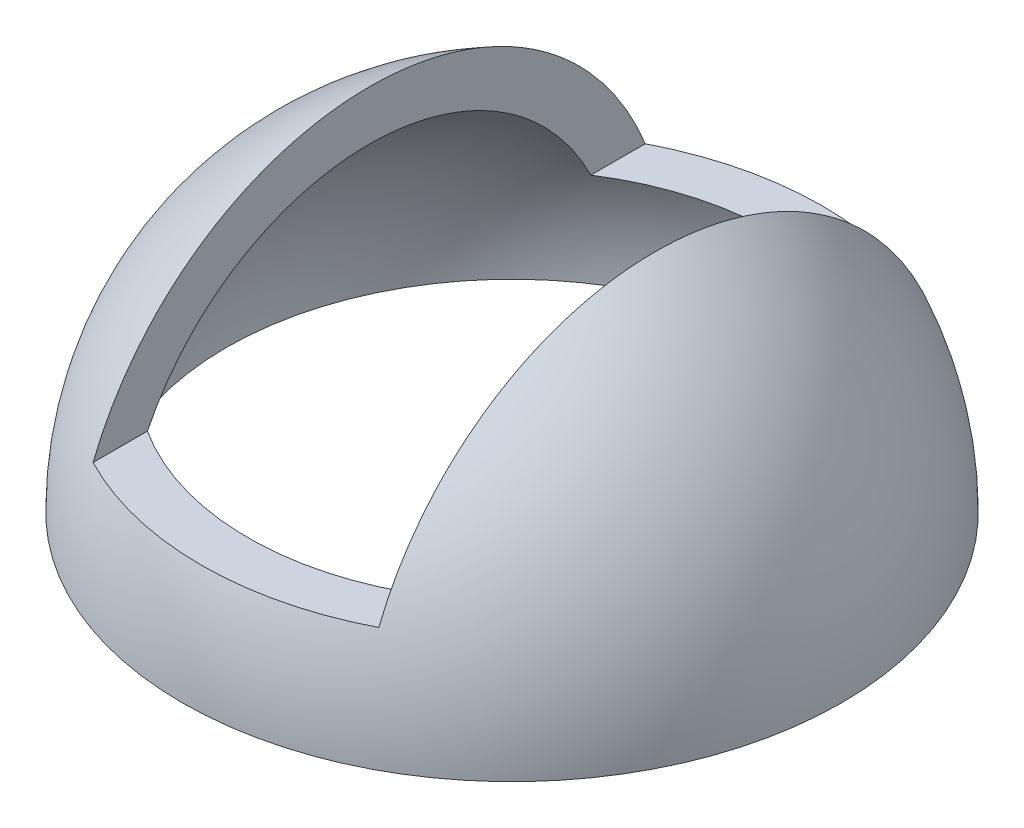
SolidWorks part; units mm, degrees
ref_plane "Front Plane" through (0, 0, 0) normal (0, 0, 1) x (1, 0, 0)
ref_plane "Top Plane" through (0, 0, 0) normal (0, 1, 0) x (1, 0, 0)
ref_plane "Right Plane" through (0, 0, 0) normal (1, 0, 0) x (0, 0, -1)
sketch "Sketch1" plane through (0, 0, 0) normal (0, 0, 1) x (1, 0, 0)
  line L0 (16.51, 0) -> (19.05, 0) construction
  line L1 (19.05, 0) -> (16.51, 0) construction
  line L2 (19.05, 0) -> (16.51, 0)
  line L3 (0, 19.05) -> (0, 16.51)
  arc A0 (19.05, 0) -> (0, 19.05) centre (0, 0) ccw
  arc A2 (16.51, 0) -> (0, 16.51) centre (0, 0) ccw
  circle A3 centre (0, 0) radius 19.05 construction
  circle A4 centre (0, 0) radius 16.51 construction
  dimension "D1" = 38.1
  dimension "D2" = 2.54
revolve "Revolve1" add sketch "Sketch1" angle 360 about L3
sketch "Sketch2" plane through (0, 0, 0) normal (0, 0, 1) x (1, 0, 0)
  line L0 (0, 6.35) -> (0, 0) construction
  line L1 (-8.255, 22.7688) -> (8.255, 22.7688)
  line L2 (-8.255, 22.7688) -> (-8.255, 6.35)
  line L3 (-8.255, 6.35) -> (8.255, 6.35)
  line L4 (8.255, 22.7688) -> (8.255, 6.35)
  dimension "D1" = 6.35
  dimension "D2" = 16.51
extrude "Cut-Extrude1" cut sketch "Sketch2" against normal mid plane 127
